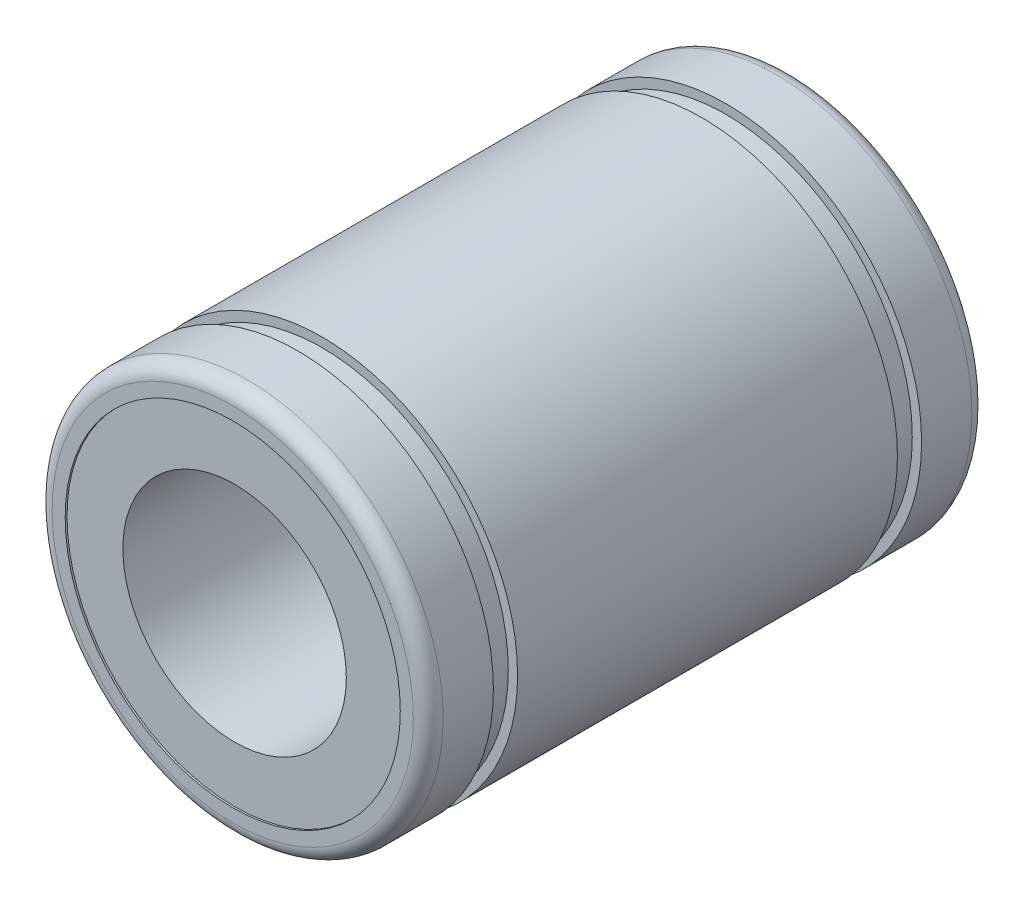
SolidWorks part; units mm, degrees
material "5052-H32"
ref_plane "Plano frontal" through (0, 0, 0) normal (0, 0, 1) x (1, 0, 0)
ref_plane "Plano superior" through (0, 0, 0) normal (0, 1, 0) x (1, 0, 0)
ref_plane "Plano direito" through (0, 0, 0) normal (1, 0, 0) x (0, 0, -1)
sketch "Esboço1" plane through (0, 0, 0) normal (0, 1, 0) x (1, 0, 0)
  line L0 (9.7, -3) -> (6, -3)
  line L1 (6, -3) -> (6, -33)
  line L2 (6, -33) -> (9.7, -33)
  line L3 (10.5, -32.2) -> (10.5, -29.5)
  line L4 (10.5, -29.5) -> (10, -29.5)
  line L5 (10, -29.5) -> (10, -28.2)
  line L6 (10, -28.2) -> (10.5, -28.2)
  line L7 (10.5, -28.2) -> (10.5, -7.8)
  line L8 (10.5, -7.8) -> (10, -7.8)
  line L9 (10, -7.8) -> (10, -6.5)
  line L10 (10, -6.5) -> (10.5, -6.5)
  line L11 (10.5, -6.5) -> (10.5, -3.8)
  line L12 (0, -2.9987) -> (0, -33.0013) construction
  arc A0 (9.7, -33) -> (10.5, -32.2) centre (9.7, -32.2) ccw
  arc A1 (10.5, -3.8) -> (9.7, -3) centre (9.7, -3.8) ccw
  dimension "D1" = 30
revolve "Revolução1" add sketch "Esboço1" angle 360 about L12
sketch "Esboço2" plane through (0, 0, 33) normal (0, 0, 1) x (1, 0, 0)
  circle A0 centre (0, 0) radius 9
extrude "Corte-extrusão1" cut sketch "Esboço2" against normal blind 0.1
sketch "Esboço3" plane through (0, 0, 3) normal (0, 0, -1) x (-1, 0, 0)
  circle A0 centre (0, 0) radius 9
extrude "Corte-extrusão2" cut sketch "Esboço3" against normal blind 0.1
